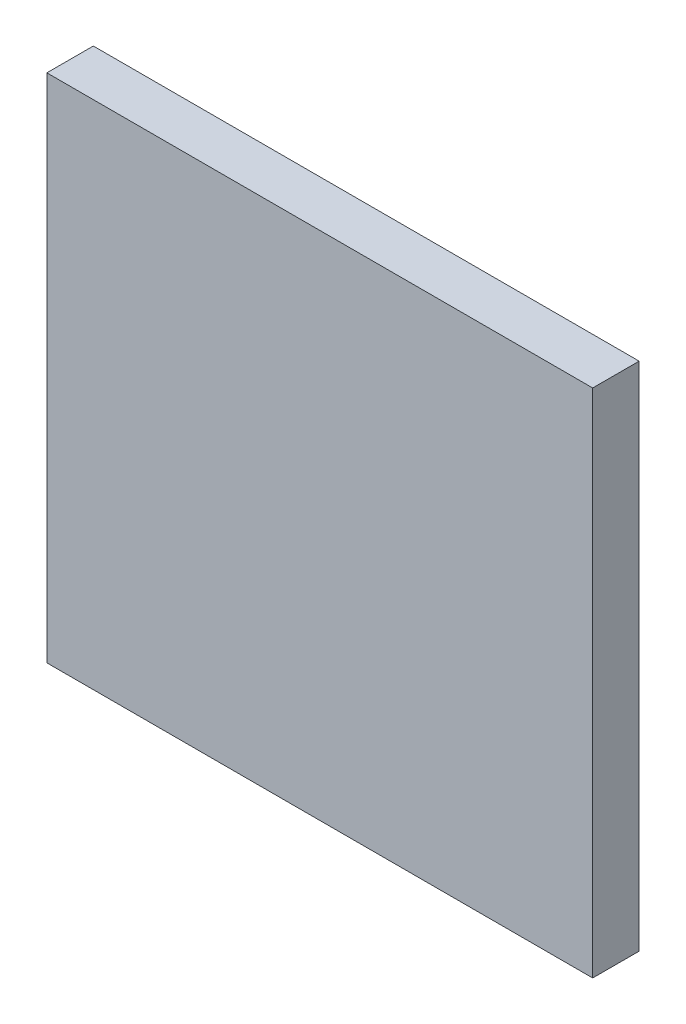
SolidWorks part; units mm, degrees
ref_plane "Plan de face" through (0, 0, 0) normal (0, 0, 1) x (1, 0, 0)
ref_plane "Plan de dessus" through (0, 0, 0) normal (0, 1, 0) x (1, 0, 0)
ref_plane "Plan de droite" through (0, 0, 0) normal (1, 0, 0) x (0, 0, -1)
sketch "Esquisse1" plane through (0, 0, 0) normal (0, 0, 1) x (1, 0, 0)
  line L0 (-23.5, 22) -> (23.5, -22) construction
  line L1 (-23.5, 22) -> (23.5, 22)
  line L2 (-23.5, 22) -> (-23.5, -22)
  line L3 (-23.5, -22) -> (23.5, -22)
  line L4 (23.5, 22) -> (23.5, -22)
  point P4 (0, 0)
  dimension "D1" = 47
  dimension "D2" = 44
extrude "Boss.-Extru.1" add sketch "Esquisse1" along normal blind 4
